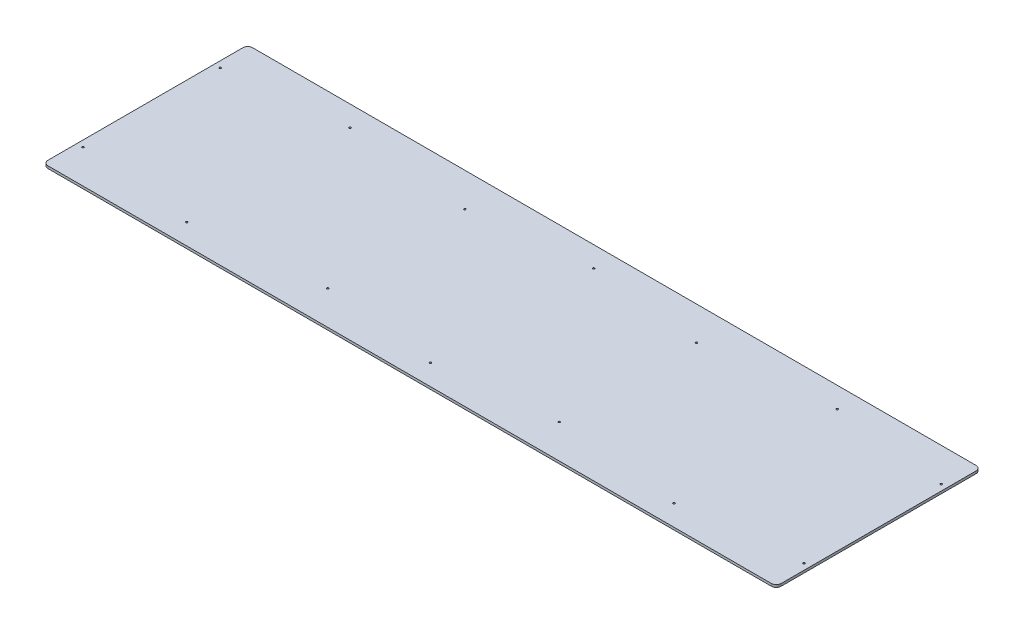
SolidWorks part; units mm, degrees
material "PE High Density"
ref_plane "Front Plane" through (0, 0, 0) normal (0, 0, 1) x (1, 0, 0)
ref_plane "Top Plane" through (0, 0, 0) normal (0, 1, 0) x (1, 0, 0)
ref_plane "Right Plane" through (0, 0, 0) normal (1, 0, 0) x (0, 0, -1)
sketch "Sketch1" plane through (0, 0, 0) normal (0, 1, 0) x (1, 0, 0)
  line L1 (0, 0) -> (1911.35, 0)
  line L2 (0, 0) -> (0, 533.4)
  line L3 (0, 533.4) -> (1911.35, 533.4)
  line L4 (1911.35, 0) -> (1911.35, 533.4)
  dimension "D1" = 1911.35
  dimension "D2" = 533.4
extrude "Boss-Extrude1" add sketch "Sketch1" along normal blind 6.35
sketch "Sketch2" plane through (0, 6.35, 0) normal (0, 1, 0) x (1, 0, 0)
  line L0 (1911.35, 533.4) -> (0, 533.4) construction
  line L2 (0, 533.4) -> (0, 0) construction
  line L3 (955.675, 533.4) -> (955.675, 0) construction
  line L4 (0, 0) -> (1911.35, 0) construction
  circle A0 centre (15.875, 445.643) radius 2.4511
  circle A1 centre (653.9653, 445.643) radius 2.4511
  circle A2 centre (653.9653, 88.011) radius 2.4511
  circle A3 centre (15.875, 88.011) radius 2.4511
  circle A4 centre (1257.3847, 445.643) radius 2.4511
  circle A5 centre (1257.3847, 88.011) radius 2.4511
  circle A6 centre (1895.475, 445.643) radius 2.4511
  circle A7 centre (1895.475, 88.011) radius 2.4511
  point P0 (15.875, 445.643)
  point P5 (653.9653, 445.643)
  point P10 (653.9653, 88.011)
  point P17 (15.875, 88.011)
  point P20 (1292.0557, 445.643)
  point P21 (1292.0557, 88.011)
  point P22 (1930.146, 88.011)
  point P23 (1930.146, 445.643)
  point P24 (1257.3847, 445.643)
  point P25 (1257.3847, 88.011)
  point P26 (1895.475, 88.011)
  point P27 (1895.475, 445.643)
  dimension "D7" = 4.9022
  dimension "D1" = 87.757
  dimension "D2" = 4
  dimension "D3" = 2
  dimension "D4" = 638.0903
  dimension "D5" = 15.875
  dimension "D6" = 357.632
sketch "Sketch7" plane through (0, 6.35, 0) normal (0, 1, 0) x (1, 0, 0)
  line L0 (0, 533.4) -> (0, 0) construction
  line L1 (1911.35, 533.4) -> (0, 533.4) construction
  circle A0 centre (320.675, 479.425) radius 2.4511
  circle A1 centre (320.675, 53.975) radius 2.4511
  circle A2 centre (955.675, 53.975) radius 2.4511
  circle A3 centre (955.675, 479.425) radius 2.4511
  circle A4 centre (1590.675, 479.425) radius 2.4511
  circle A5 centre (1590.675, 53.975) radius 2.4511
  point P0 (320.675, 479.425)
  point P8 (955.675, 479.425)
  point P9 (1590.675, 479.425)
  point P13 (955.675, 53.975)
  point P14 (1590.675, 53.975)
  point P18 (320.675, 53.975)
  dimension "D7" = 4.9022
  dimension "D1" = 320.675
  dimension "D2" = 53.975
  dimension "D5" = 635
  dimension "D6" = 425.45
  dimension "D3" = 3
  dimension "D4" = 2
fillet "Fillet1" radius 12.7 4 edges at (1911.35, 3.175, 0) (1911.35, 3.175, -533.4) (0, 3.175, 0) (0, 3.175, -533.4)
extrude "Cut-Extrude1" cut sketch "Sketch2" against normal blind 6.35
extrude "Cut-Extrude2" cut sketch "Sketch7" against normal blind 6.35
